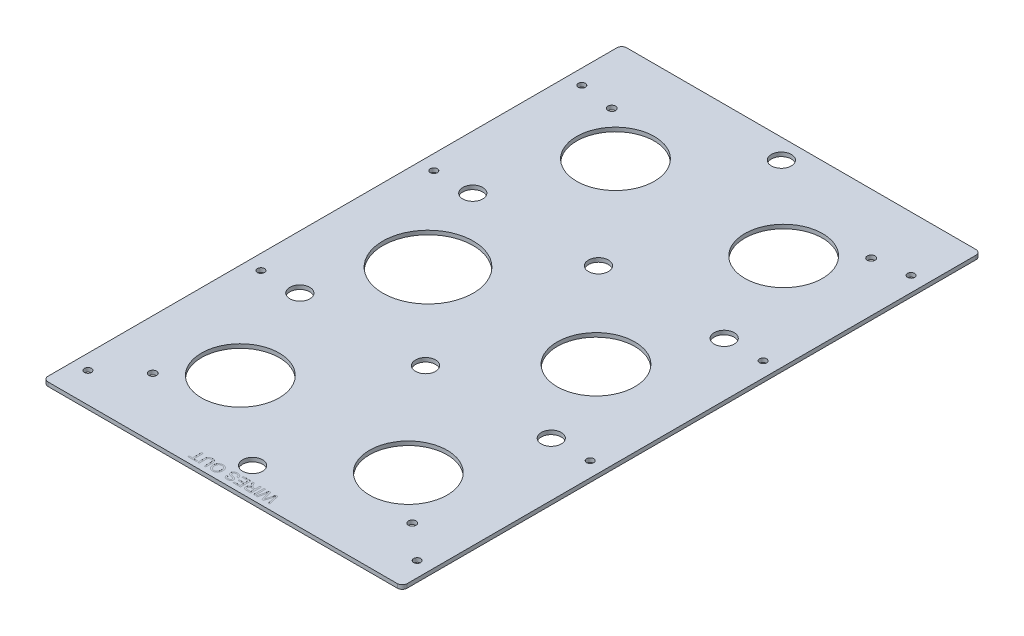
SolidWorks part; units mm, degrees
ref_plane "Front" through (0, 0, 0) normal (0, 0, 1) x (1, 0, 0)
ref_plane "Top" through (0, 0, 0) normal (0, 1, 0) x (1, 0, 0)
ref_plane "Right" through (0, 0, 0) normal (1, 0, 0) x (0, 0, -1)
sketch "Sketch1" plane through (0, 0, 0) normal (0, 1, 0) x (1, 0, 0)
  line L0 (-23.1141, -90.9347) -> (-23.2411, -90.9347) construction
  line L1 (-56.1213, 212.5953) -> (166.1287, 212.5953)
  line L2 (-59.2963, 209.4203) -> (-59.2963, -152.5297)
  line L3 (-56.1213, -155.7047) -> (166.1287, -155.7047)
  line L4 (169.3037, 209.4203) -> (169.3037, -152.5297)
  line L5 (-59.2963, 212.5953) -> (169.3037, -155.7047) construction
  line L6 (-59.2963, -155.7047) -> (169.3037, 212.5953) construction
  line L7 (-18.11, 48.5096) -> (21.0818, 8.5096) construction
  line L8 (81.9912, -155.7047) -> (166.1287, -155.7047) construction
  line L9 (169.3037, -152.5297) -> (169.3037, 209.4203) construction
  circle A0 centre (108.5215, -91.0633) radius 24.727
  circle A1 centre (108.5215, 28.381) radius 24.727
  circle A2 centre (1.4859, -90.9347) radius 24.727
  circle A4 centre (1.4859, 147.8253) radius 24.727
  circle A5 centre (108.5215, 147.8253) radius 24.727
  arc A6 (6.4427, -115.0302) -> (4.0942, -66.4734) centre (1.4859, -90.9347) ccw construction
  arc A7 (6.4427, -115.0302) -> (-3.4709, -66.8393) centre (1.4859, -90.9347) ccw construction
  arc A8 (169.3037, 209.4203) -> (166.1287, 212.5953) centre (166.1287, 209.4203) ccw
  arc A9 (-59.2963, 209.4203) -> (-56.1213, 212.5953) centre (-56.1213, 209.4203) cw
  arc A10 (-59.2963, -152.5297) -> (-56.1213, -155.7047) centre (-56.1213, -152.5297) ccw
  arc A11 (166.1287, -155.7047) -> (169.3037, -152.5297) centre (166.1287, -152.5297) ccw
  circle A12 centre (1.4859, 28.5096) radius 28.7693
  circle A13 centre (-25.0063, -26.5838) radius 2.2479 construction
  circle A14 centre (-25.0063, -26.5838) radius 2.2479 construction
  circle A15 centre (55.0037, -26.5881) radius 2.2479 construction
  circle A16 centre (55.0037, -26.5881) radius 2.2479 construction
  circle A17 centre (135.0137, -26.5838) radius 2.2479 construction
  circle A18 centre (135.0137, -26.5838) radius 2.2479 construction
  circle A19 centre (135.0137, 83.4744) radius 2.2479 construction
  circle A20 centre (135.0137, 83.4744) radius 2.2479 construction
  circle A21 centre (55.0037, 83.4786) radius 2.2479 construction
  circle A22 centre (55.0037, 83.4786) radius 2.2479 construction
  circle A23 centre (-25.0063, 83.4744) radius 2.2479 construction
  circle A24 centre (-25.0063, 83.4744) radius 2.2479 construction
  circle A25 centre (55.0037, 199.8953) radius 2.2479 construction
  circle A26 centre (55.0037, 199.8953) radius 2.2479 construction
  circle A27 centre (55.0037, -136.6547) radius 2.2479 construction
  circle A28 centre (55.0037, -136.6547) radius 2.2479 construction
  circle A29 centre (55.0037, -136.6547) radius 6.35
  circle A30 centre (135.0137, -26.5838) radius 6.35
  circle A31 centre (55.0037, -26.5881) radius 6.35
  circle A32 centre (-25.0063, -26.5838) radius 6.35
  circle A33 centre (135.0137, 83.4744) radius 6.35
  circle A34 centre (55.0037, 83.4786) radius 6.35
  circle A35 centre (-25.0063, 83.4744) radius 6.35
  circle A36 centre (55.0037, 199.8953) radius 6.35
  circle A37 centre (137.5537, 174.4953) radius 2.4574 construction
  circle A38 centre (137.5537, 174.4953) radius 2.4574
  circle A39 centre (-27.5463, 174.4953) radius 2.4575 construction
  circle A40 centre (-27.5463, 174.4953) radius 2.4575
  circle A41 centre (-27.5463, -117.6047) radius 2.4575 construction
  circle A42 centre (-27.5463, -117.6047) radius 2.4575
  circle A43 centre (137.5537, -117.6047) radius 2.4574 construction
  circle A44 centre (137.5537, -117.6047) radius 2.4575
  circle A45 centre (-49.7713, 177.6703) radius 2.2479 construction
  circle A46 centre (-49.7713, 177.6703) radius 2.2479
  circle A47 centre (-49.7713, 83.4786) radius 2.2479 construction
  circle A48 centre (-49.7713, 83.4786) radius 2.2479
  circle A49 centre (159.7787, 177.6703) radius 2.2479 construction
  circle A50 centre (159.7787, 177.6703) radius 2.2479
  circle A51 centre (159.7787, 83.4786) radius 2.2479 construction
  circle A52 centre (159.7787, 83.4786) radius 2.2479
  circle A53 centre (159.7787, -26.5881) radius 2.2479 construction
  circle A54 centre (159.7787, -26.5881) radius 2.2479
  circle A55 centre (-49.7713, -26.5881) radius 2.2479 construction
  circle A56 centre (-49.7713, -26.5881) radius 2.2479
  circle A57 centre (-49.7713, -136.6547) radius 2.2479 construction
  circle A58 centre (-49.7713, -136.6547) radius 2.2479
  circle A59 centre (159.7787, -136.6547) radius 2.2479 construction
  circle A60 centre (159.7787, -136.6547) radius 2.2479
  point P0 (55.0037, 28.4453)
  dimension "D3" = 0.127
  dimension "D4" = 3.175
  dimension "D5" = 12.7
  dimension "D1" = 228.6
  dimension "D2" = 368.3
extrude "Boss-Extrude1" add sketch "Sketch1" along normal blind 2.54
sketch "Sketch2" plane through (0, 2.54, 0) normal (0, 1, 0) x (1, 0, 0)
  line L0 (81.7963, -145.7047) -> (81.7963, -155.7047) construction
  line L2 (81.7963, -145.7047) -> (30.9963, -145.7047) construction
  line L3 (-56.1213, -155.7047) -> (166.1287, -155.7047) construction
  line L4 (169.3037, -152.5297) -> (169.3037, 209.4203) construction
  text T0 "WIRES OUT" font "Arial" height in points 26
  dimension "D1" = 10
  dimension "D2" = 50.8
  dimension "D3" = 87.5074
extrude "Cut-Extrude2" cut sketch "Sketch2" against normal blind 0.0254
